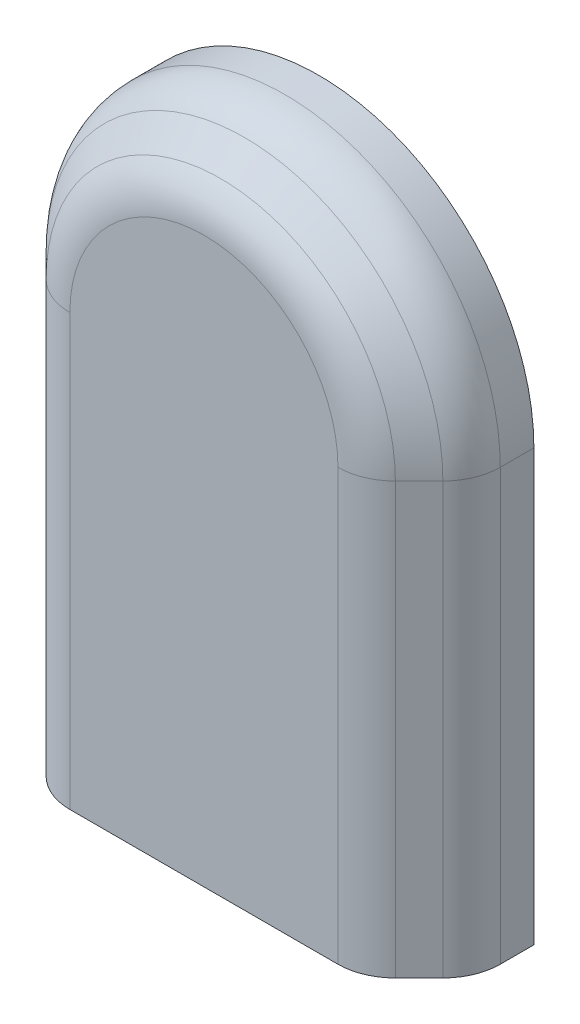
SolidWorks part; units mm, degrees
ref_plane "Front Plane" through (0, 0, 0) normal (0, 0, 1) x (1, 0, 0)
ref_plane "Top Plane" through (0, 0, 0) normal (0, 1, 0) x (1, 0, 0)
ref_plane "Right Plane" through (0, 0, 0) normal (1, 0, 0) x (0, 0, -1)
sketch "Sketch1" plane through (0, 0, 0) normal (0, 0, 1) x (1, 0, 0)
  line L0 (-37.5, 0) -> (-37.5, -100)
  line L1 (37.5, 0) -> (37.5, -100)
  line L2 (37.5, -100) -> (-37.5, -100)
  line L3 (-31.5, 0) -> (-31.5, -94)
  line L4 (31.5, -94) -> (-31.5, -94)
  line L5 (31.5, 0) -> (31.5, -94)
  arc A0 (-24.7134, 28.2046) -> (-37.5, 0) centre (0, 0) ccw construction
  arc A1 (21.2255, 30.9148) -> (-24.7134, 28.2046) centre (0, 0) ccw construction
  arc A2 (37.5, 0) -> (21.2255, 30.9148) centre (0, 0) ccw construction
  arc A3 (-37.5, 0) -> (37.5, 0) centre (0, 0) cw
  arc A5 (31.5, 0) -> (17.8294, 25.9685) centre (0, 0) ccw
  arc A6 (17.8294, 25.9685) -> (-20.7592, 23.6919) centre (0, 0) ccw
  arc A7 (-20.7592, 23.6919) -> (-31.5, 0) centre (0, 0) ccw
  point P7 (-43.0508, -109.7322)
  point P8 (0, 0)
  point P9 (0, 0)
  point P15 (0, 0)
  point P16 (0, 0)
  dimension "D3" = 37.5
  dimension "D1" = 100
  dimension "D2" = 75
  dimension "D4" = 6
extrude "Boss-Extrude1" add sketch "Sketch1" along normal blind 20 contours L1 L2 L0 A3
chamfer "Chamfer1" distance 10 angle 45 3 edges at (37.5, -50, 20) (0, 37.5, 20) (-37.5, -50, 20)
fillet "Fillet1" radius 10 3 edges at (-27.5, -50, 20) (0, 27.5, 20) (27.5, -50, 20)
shell "Shell1" [suppressed] thickness 5
sketch "Sketch2" [suppressed] plane through (0, 0, 15) normal (0, 0, -1) x (-1, 0, 0)
  line L0 (-8.75, 8.75) -> (8.75, -8.75) construction
  line L1 (-8.75, 8.75) -> (8.75, 8.75) construction
  line L2 (-8.75, 8.75) -> (-8.75, -8.75) construction
  line L3 (-8.75, -8.75) -> (8.75, -8.75) construction
  line L4 (8.75, 8.75) -> (8.75, -8.75) construction
  line L5 (8.75, 8.75) -> (-8.75, -8.75) construction
  circle A0 centre (-8.75, 8.75) radius 1
  circle A1 centre (8.75, 8.75) radius 1
  circle A2 centre (8.75, -8.75) radius 1
  circle A3 centre (-8.75, -8.75) radius 0.78
  point P4 (0, 0)
  dimension "D2" = 2
  dimension "D3" = 2
  dimension "D4" = 2
  dimension "D5" = 1.56
  dimension "D1" = 17.5
extrude "Cut-Extrude1" [suppressed] cut sketch "Sketch2" against normal through all
ref_plane "Plane1" through (0, -115, 0) normal (0, -1, 0) x (-1, 0, 0)
sketch "Sketch3" plane through (0, -115, 0) normal (0, -1, 0) x (-1, 0, 0)
  line L0 (-37.5, 0) -> (37.5, 0) construction
  line L1 (-37.5, 0) -> (37.5, 0)
  arc A0 (-37.5, 0) -> (37.5, 0) centre (0, 24.8747) ccw
  dimension "D1" = 45
sketch "Sketch4" plane through (37.5, 0, 0) normal (1, 0, 0) x (0, 0, -1)
  line L0 (0, -100) -> (0, -115) construction
  line L1 (-20.1253, -115) -> (0, -115) construction
  line L2 (-11, -115) -> (11, -115) construction
fillet "Fillet2" radius 10 3 edges at (0, 37.5, 10) (-37.5, -50, 10) (37.5, -50, 10)
sketch "Sketch5" plane through (0, -100, 0) normal (0, -1, 0) x (1, 0, 0)
  line L0 (0, 20.1253) -> (0, 0) construction
  line L1 (37.5, 0) -> (-37.5, 0)
  arc A0 (37.5, 0) -> (-37.5, 0) centre (0, -24.8747) ccw construction
  spline S0 degree 3 poles (-37.5, 0) (-38.1226, 9.0085) (-22.1466, 19.2364) (-7.3923, 19.9814) (0, 20.1253) knots 0 0 0 0 0.269912 0.503129 0.503129 0.503129 0.503129
  spline S1 degree 3 poles (37.5, 0) (38.1226, 9.0085) (22.1466, 19.2364) (7.3923, 19.9814) (0, 20.1253) knots 0 0 0 0 0.269912 0.503129 0.503129 0.503129 0.503129
ref_plane "Plane2" through (-37.5, 0, 0) normal (-1, 0, 0) x (0, 0, 1)
sketch "Sketch6" plane through (-37.5, 0, 0) normal (-1, 0, 0) x (0, 0, 1)
  line L0 (0, -100) -> (0, -115)
ref_plane "Plane3" through (0, 0, 20) normal (0, 0, 1) x (1, 0, 0)
sketch "Sketch7" plane through (0, 0, 20) normal (0, 0, 1) x (1, 0, 0)
  line L0 (0, -100) -> (0, -114.7683)
  line L1 (23.3579, -100) -> (-23.3579, -100) construction
sketch "Sketch9" plane through (0, 0, 0) normal (0, 0, -1) x (-1, 0, 0)
  line L0 (-52.5, -75) -> (52.5, -75)
  line L1 (52.5, -75) -> (52.5, -105)
  line L2 (52.5, -105) -> (-52.5, -105)
  line L3 (-52.5, -105) -> (-52.5, -75)
  line L5 (-37.5, 0) -> (-37.5, -100) construction
  line L6 (37.5, -3.2218) -> (37.5, 3.2218) construction
  dimension "D1" = 5
  dimension "D2" = 30
  dimension "D3" = 15
  dimension "D4" = 15
extrude "Cut-Extrude2" cut sketch "Sketch9" against normal through all
